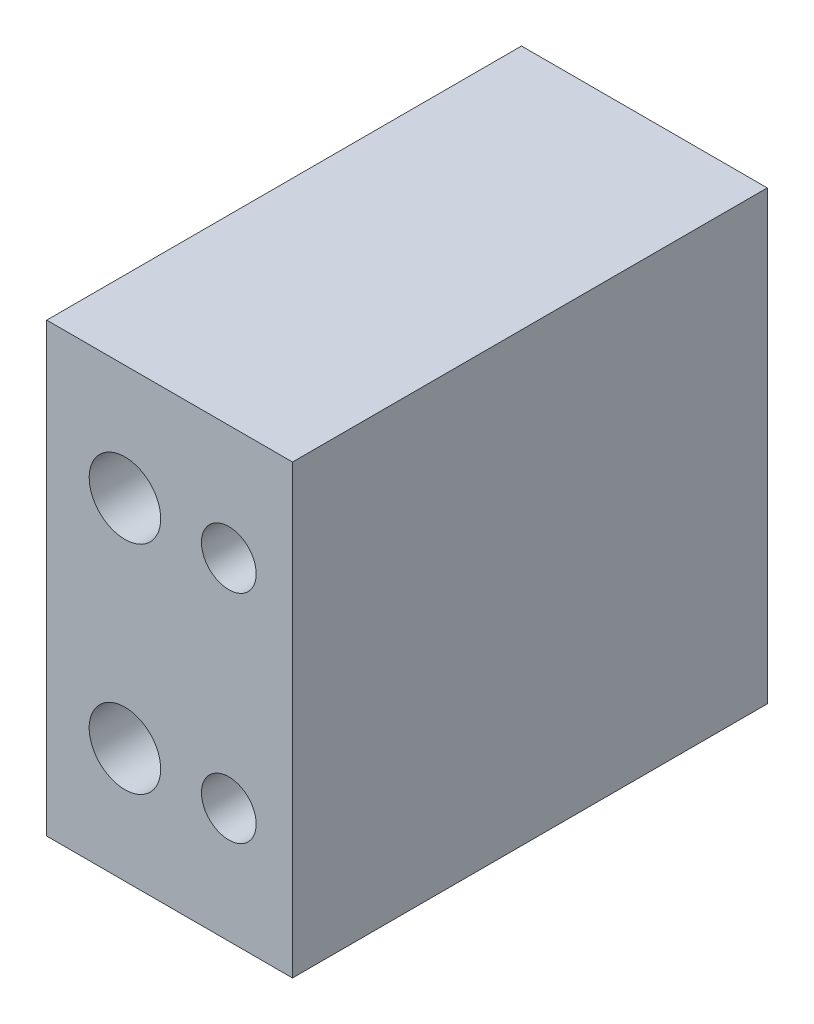
SolidWorks part; units mm, degrees
ref_plane "前视基准面" through (0, 0, 0) normal (0, 0, 1) x (1, 0, 0)
ref_plane "上视基准面" through (0, 0, 0) normal (0, 1, 0) x (1, 0, 0)
ref_plane "右视基准面" through (0, 0, 0) normal (1, 0, 0) x (0, 0, -1)
sketch "草图2" plane through (0, 0, 0) normal (0, 0, 1) x (1, 0, 0)
  line B0 (0, 0) -> (11, 0)
  line B1 (11, 20) -> (0, 20)
  line B2 (11, 0) -> (11, 20)
  line B3 (0, 0) -> (0, 20)
  circle B4 centre (8.15, 5.15) radius 1.25
  circle B5 centre (8.15, 14.85) radius 1.25
  circle B6 centre (3.5, 14.85) radius 1.5
  circle B7 centre (3.5, 5.15) radius 1.5
sketch_block_instance "块2-1"
sketch_block "块2"
sketch "草图3" plane through (0, 0, 0) normal (0, 0, 1) x (1, 0, 0)
  line L1 (0, 20) -> (11, 20)
  line L2 (0, 20) -> (0, 0)
  line L3 (0, 0) -> (11, 0)
  line L4 (11, 20) -> (11, 0)
  circle A0 centre (3.5, 14.85) radius 1.6
  circle A1 centre (3.5, 5.15) radius 1.6
  circle A2 centre (8.15, 14.85) radius 1.225
  circle A3 centre (8.15, 5.15) radius 1.225
  dimension "D1" = 2.45
  dimension "D2" = 3.2
extrude "凸台-拉伸1" add sketch "草图3" along normal blind 21.25
sketch "草图4" plane through (0, 0, 0) normal (-1, 0, 0) x (0, 0, 1)
  line L0 (0, 20) -> (0, 0) construction
  line L1 (3, 17.7) -> (6, 17.7)
  line L2 (3, 17.7) -> (3, 12)
  line L3 (3, 12) -> (6, 12)
  line L4 (6, 17.7) -> (6, 12)
  line L5 (3, 8) -> (6, 8)
  line L6 (3, 8) -> (3, 2.3)
  line L7 (3, 2.3) -> (6, 2.3)
  line L8 (6, 8) -> (6, 2.3)
  line L9 (21.25, 20) -> (0, 20) construction
  line L10 (21.25, 0) -> (0, 0) construction
  dimension "D1" = 3
  dimension "D2" = 2.3
  dimension "D3" = 5.7
  dimension "D4" = 3
  dimension "D5" = 5.7
  dimension "D6" = 2.3
extrude "切除-拉伸1" cut sketch "草图4" against normal blind 7.1
